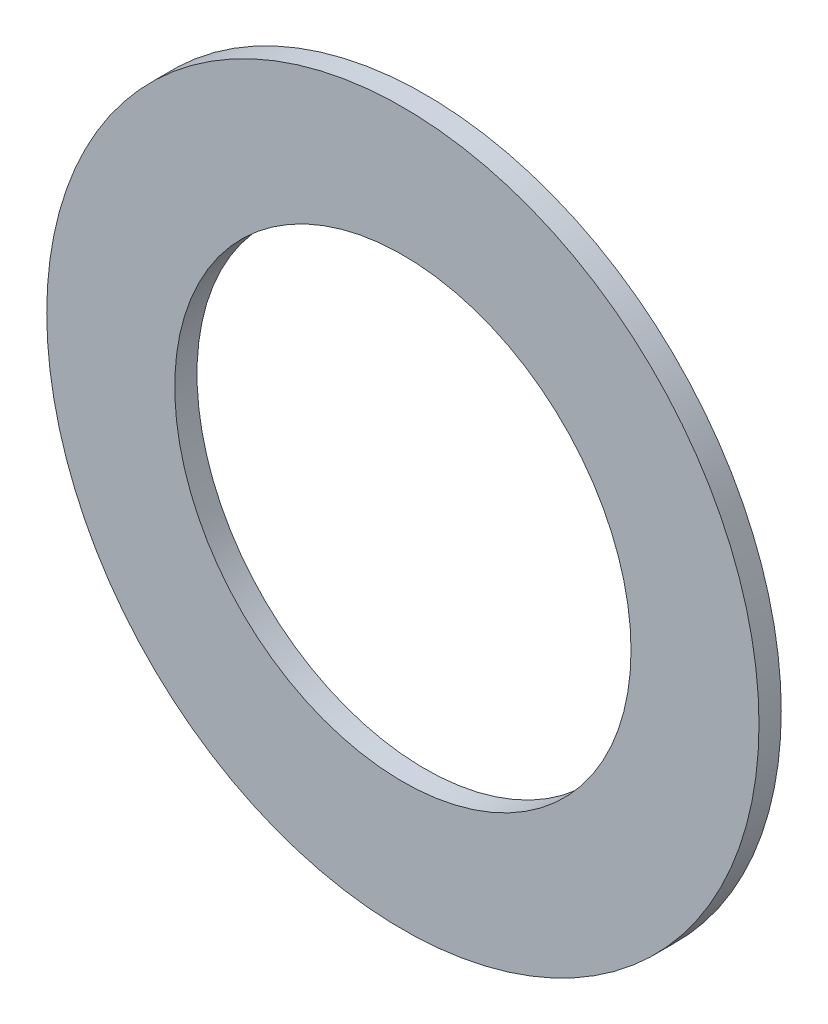
SolidWorks part; units mm, degrees
ref_plane "Front Plane" through (0, 0, 0) normal (0, 0, 1) x (1, 0, 0)
ref_plane "Top Plane" through (0, 0, 0) normal (0, 1, 0) x (1, 0, 0)
ref_plane "Right Plane" through (0, 0, 0) normal (1, 0, 0) x (0, 0, -1)
sketch "Sketch1" plane through (0, 0, 0) normal (0, 0, 1) x (1, 0, 0)
  circle A0 centre (0, 0) radius 10.25
  circle A1 centre (0, 0) radius 16
extrude "Boss-Extrude1" add sketch "Sketch1" along normal blind 1
